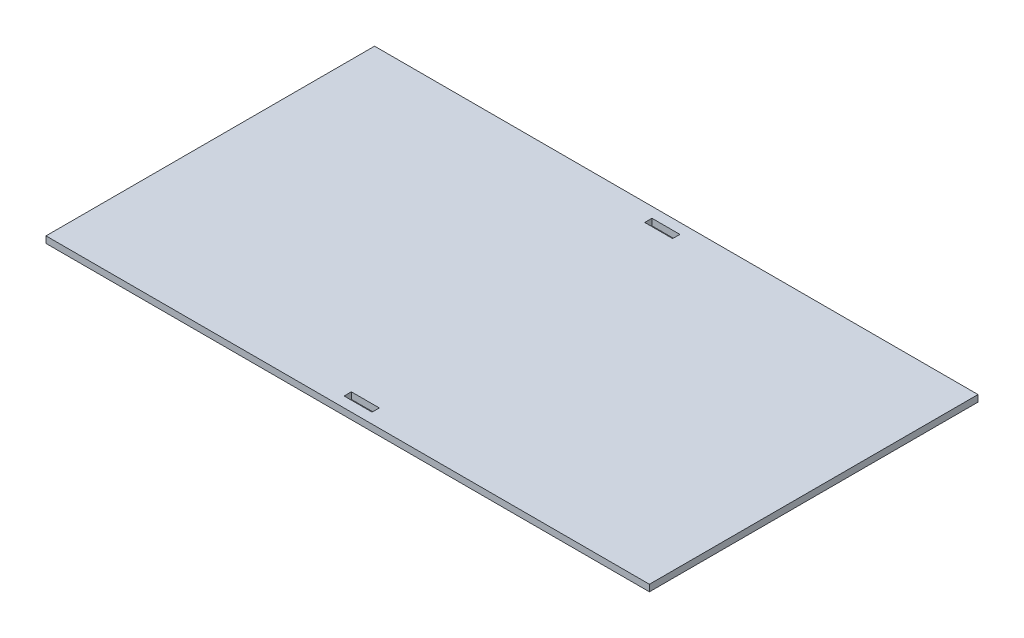
SolidWorks part; units mm, degrees
material "Acrylic (Medium-high impact)"
ref_plane "Front Plane" through (0, 0, 0) normal (0, 0, 1) x (1, 0, 0)
ref_plane "Top Plane" through (0, 0, 0) normal (0, 1, 0) x (1, 0, 0)
ref_plane "Right Plane" through (0, 0, 0) normal (1, 0, 0) x (0, 0, -1)
sketch "Sketch1" plane through (0, 0, 0) normal (0, 1, 0) x (1, 0, 0)
  line L0 (-137.16, 66.675) -> (137.16, 66.675) construction
  line L1 (137.16, 74.6887) -> (-137.16, 74.6887)
  line L2 (137.16, 74.6887) -> (137.16, -74.6887)
  line L3 (137.16, -74.6887) -> (-137.16, -74.6887)
  line L4 (-137.16, 74.6887) -> (-137.16, -74.6887)
  line L5 (137.16, 74.6887) -> (-137.16, -74.6887) construction
  line L6 (137.16, -74.6887) -> (-137.16, 74.6887) construction
  line L7 (-137.16, -66.675) -> (137.16, -66.675) construction
  line L8 (0, -66.675) -> (0, 66.675) construction
  line L10 (-6.35, 66.675) -> (6.35, 66.675)
  line L11 (-6.35, 66.675) -> (-6.35, 69.977)
  line L12 (-6.35, 69.977) -> (6.35, 69.977)
  line L13 (6.35, 66.675) -> (6.35, 69.977)
  line L14 (-6.35, -66.675) -> (6.35, -66.675)
  line L15 (-6.35, -66.675) -> (-6.35, -69.977)
  line L16 (-6.35, -69.977) -> (6.35, -69.977)
  line L17 (6.35, -66.675) -> (6.35, -69.977)
  point P0 (0, 0)
  point P13 (0, 0)
  point P22 (0, 66.675)
  dimension "D1" = 274.32
  dimension "D2" = 149.3774
  dimension "D4" = 3.302
  dimension "D5" = 12.7
  dimension "D3" = 133.35
extrude "Boss-Extrude1" add sketch "Sketch1" along normal blind 2.9972
equation "\"WallThickness\"=0.125"
equation "\"D3@Sketch1\"=\"WallThickness\"*2+5"
